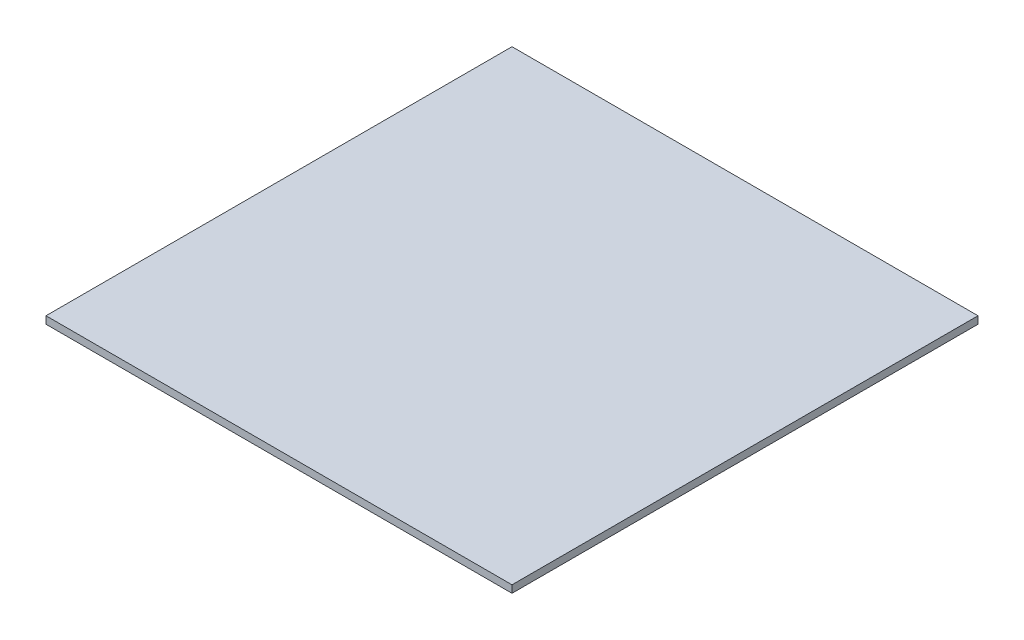
SolidWorks part; units mm, degrees
ref_plane "Front Plane" through (0, 0, 0) normal (0, 0, 1) x (1, 0, 0)
ref_plane "Top Plane" through (0, 0, 0) normal (0, 1, 0) x (1, 0, 0)
ref_plane "Right Plane" through (0, 0, 0) normal (1, 0, 0) x (0, 0, -1)
sketch "Sketch1" plane through (0, 0, 0) normal (0, 1, 0) x (1, 0, 0)
  line L1 (0, 0) -> (360, 0)
  line L2 (0, 0) -> (0, 360)
  line L3 (0, 360) -> (360, 360)
  line L4 (360, 0) -> (360, 360)
  line L5 (0, 0) -> (360, 360) construction
  line L6 (0, 360) -> (360, 0) construction
  point P4 (180, 180)
  dimension "D1" = 360
  dimension "D2" = 360
extrude "Boss-Extrude1" add sketch "Sketch1" along normal blind 5.7
